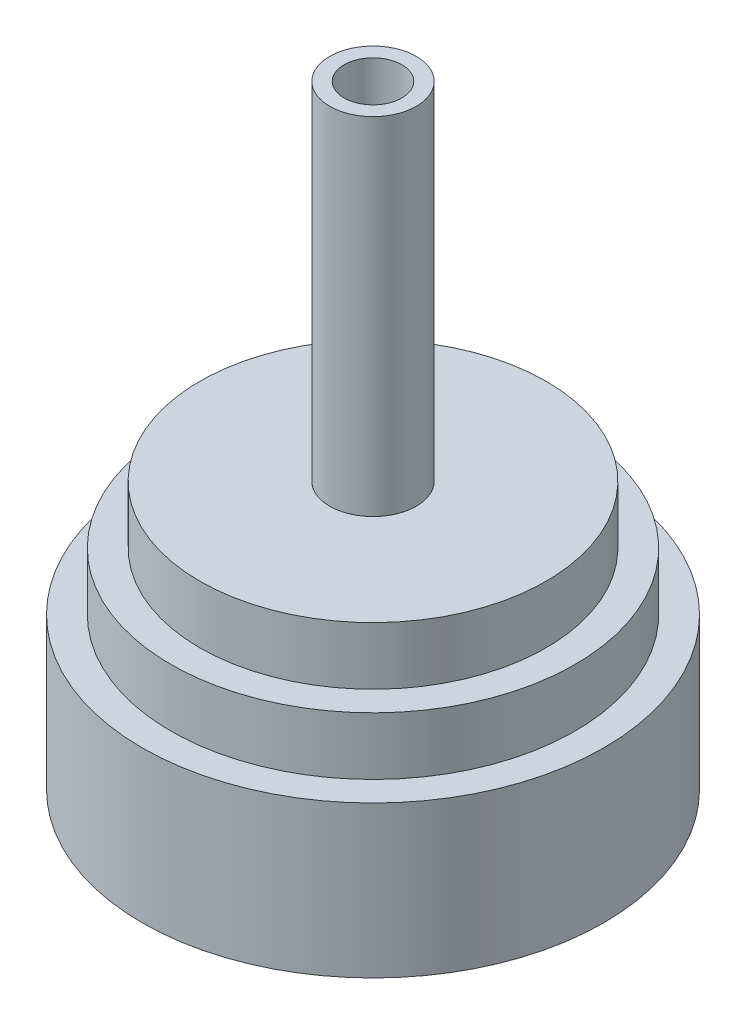
SolidWorks part; units mm, degrees
ref_plane "Front Plane" through (0, 0, 0) normal (0, 0, 1) x (1, 0, 0)
ref_plane "Top Plane" through (0, 0, 0) normal (0, 1, 0) x (1, 0, 0)
ref_plane "Right Plane" through (0, 0, 0) normal (1, 0, 0) x (0, 0, -1)
sketch "Sketch3" plane through (0, 0, 0) normal (0, 1, 0) x (1, 0, 0)
  circle A0 centre (0, 0) radius 7.5
  circle A1 centre (0, 0) radius 5
  dimension "D1" = 15
  dimension "D2" = 10
extrude "Boss-Extrude1" add sketch "Sketch3" along normal blind 60
sketch "Sketch4" plane through (0, 0, 0) normal (1, 0, 0) x (0, 0, -1)
  line L0 (7.5, 0) -> (30, 0)
  line L1 (30, 0) -> (30, -10)
  line L2 (30, -10) -> (35, -10)
  line L3 (35, -10) -> (35, -20)
  line L4 (35, -20) -> (40, -20)
  line L5 (40, -20) -> (40, -46.2487)
  line L7 (30, -40) -> (30, -15)
  line L8 (30, -15) -> (7.5, -15)
  line L9 (7.5, -15) -> (7.5, 0)
  line L10 (0, 0) -> (0, 21.1194) construction
  line L11 (30, -40) -> (40, -46.2487)
  line L12 (30, -40) -> (37.0632, -40) construction
  dimension "D1" = 30
  dimension "D2" = 15
  dimension "D3" = 32
  dimension "D4" = 5
  dimension "D5" = 10
  dimension "D6" = 5
  dimension "D7" = 10
  dimension "D8" = 10
  dimension "D9" = 22.5
  dimension "D10" = 40
  dimension "D11" = 25
revolve "Revolve1" add sketch "Sketch4" angle 360 about L10
